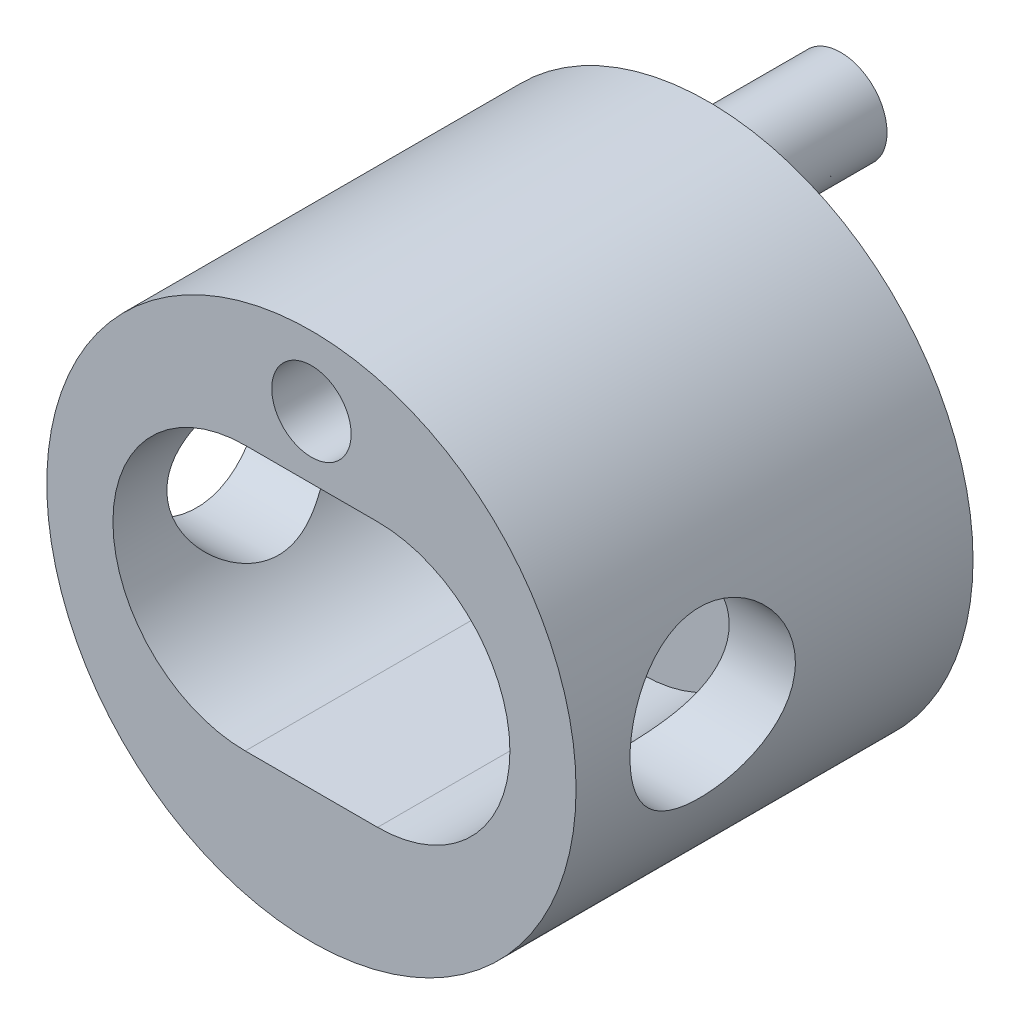
SolidWorks part; units mm, degrees
ref_plane "Front Plane" through (0, 0, 0) normal (0, 0, 1) x (1, 0, 0)
ref_plane "Top Plane" through (0, 0, 0) normal (0, 1, 0) x (1, 0, 0)
ref_plane "Right Plane" through (0, 0, 0) normal (1, 0, 0) x (0, 0, -1)
sketch "Sketch1" plane through (0, 0, 0) normal (0, 0, 1) x (1, 0, 0)
  circle A0 centre (0, 0) radius 20
  dimension "D1" = 40
extrude "Boss-Extrude1" add sketch "Sketch1" along normal blind 30
sketch "Sketch2" plane through (0, 0, 30) normal (0, 0, 1) x (1, 0, 0)
  line L0 (-20, 0) -> (20, 0) construction
  line L1 (-5, 0) -> (5, 0) construction
  line L2 (-5, 10) -> (5, 10)
  line L3 (-5, -10) -> (5, -10)
  circle A0 centre (0, 0) radius 20 construction
  arc A1 (-5, 10) -> (-5, -10) centre (-5, 0) ccw
  arc A2 (5, -10) -> (5, 10) centre (5, 0) ccw
  point P7 (0, 0)
  dimension "D1" = 10
  dimension "D2" = 10
extrude "Cut-Extrude1" cut sketch "Sketch2" against normal blind 20
sketch "Sketch3" plane through (0, 0, 30) normal (0, 0, 1) x (1, 0, 0)
  line L0 (0, 20) -> (0, -20) construction
  circle A0 centre (0, 0) radius 20 construction
  circle A1 centre (0, 14.723) radius 3
  point P7 (0, 7.563)
  point P8 (0, 14.723)
  dimension "D1" = 6
extrude "Cut-Extrude2" cut sketch "Sketch3" against normal blind 35
sketch "Sketch4" plane through (0, 0, 0) normal (1, 0, 0) x (0, 0, -1)
  circle A0 centre (-19.6762, 0) radius 6.25
  point P2 (-10.924, 0)
  point P3 (-12.0024, 0)
  point P4 (0, 0)
  point P5 (-15.9931, 0)
  point P6 (-19.6762, 0)
  dimension "D1" = 12.5
extrude "Cut-Extrude3" cut sketch "Sketch4" against normal blind 31 and the other way blind 28 contours A0
sketch "Sketch5" plane through (0, 0, 0) normal (0, 0, -1) x (-1, 0, 0)
  line L0 (0, 20) -> (0, -20) construction
  circle A0 centre (0, 0) radius 20 construction
  circle A1 centre (0, 0) radius 2.3
  point P7 (0, -15.5891)
  point P8 (0, 0)
  dimension "D1" = 4.6
extrude "Cut-Extrude4" cut sketch "Sketch5" against normal blind 30
sketch "Sketch9" plane through (0, 0, 0) normal (0, 0, -1) x (-1, 0, 0)
  circle A0 centre (0, 14.723) radius 3.5
  dimension "D1" = 7
extrude "Boss-Extrude4" add sketch "Sketch9" along normal blind 10 contours A0
sketch "Sketch11" plane through (0, 0, -10) normal (0, 0, -1) x (-1, 0, 0)
  circle A0 centre (0, 14.723) radius 3
  dimension "D1" = 6
extrude "Cut-Extrude6" cut sketch "Sketch11" against normal blind 10
